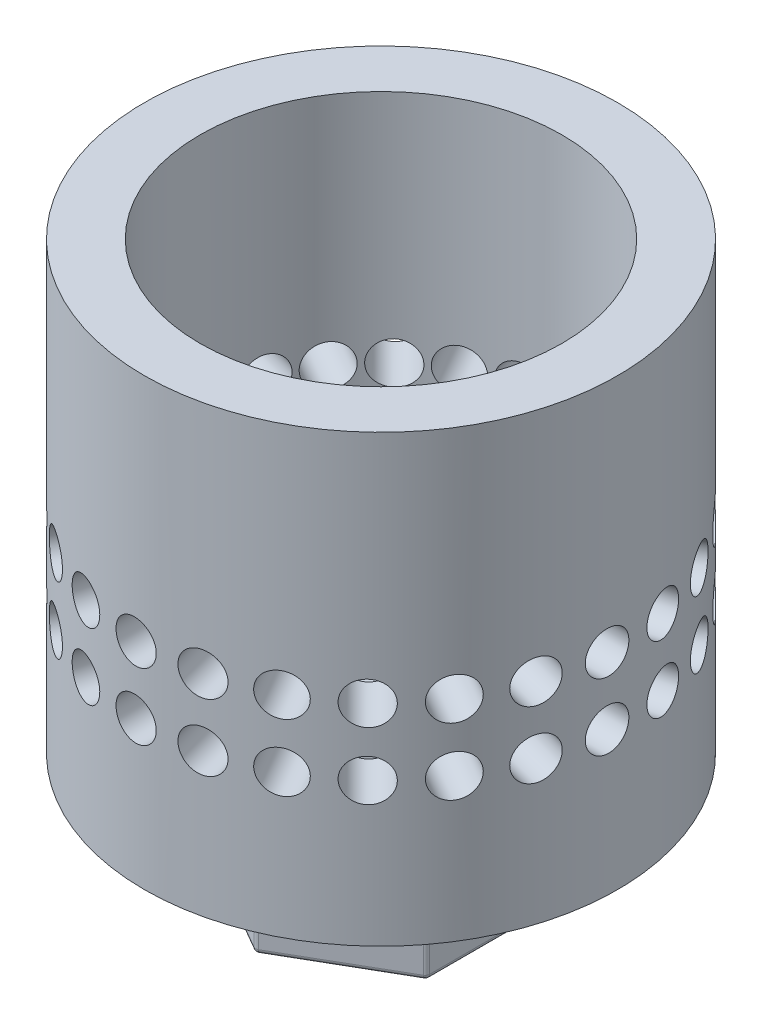
SolidWorks part; units mm, degrees
material "AISI 304"
ref_plane "Front Plane" through (0, 0, 0) normal (0, 0, 1) x (1, 0, 0)
ref_plane "Top Plane" through (0, 0, 0) normal (0, 1, 0) x (1, 0, 0)
ref_plane "Right Plane" through (0, 0, 0) normal (1, 0, 0) x (0, 0, -1)
sketch "Sketch1" plane through (0, 0, 0) normal (0, 1, 0) x (1, 0, 0)
  circle A0 centre (0, 0) radius 13.5
  dimension "D1" = 27
extrude "Boss-Extrude1" add sketch "Sketch1" along normal blind 25.4
hole_wizard "7/8-14 Tapped Hole1" positions "Sketch4" profile "Sketch5" tap size "7/8-14" standard "ANSI Inch"
sketch "Sketch4" plane through (0, 25.4, 0) normal (0, 1, 0) x (1, 0, 0)
  point P0 (0, 0)
sketch "Sketch5" plane through (0, 25.4, 0) normal (1, 0, 0) x (0, 0, 1)
  line L0 (0, 0) -> (0, 25.2501)
  line L1 (0, 25.2501) -> (10.3187, 19.05)
  line L2 (10.3187, 19.05) -> (10.3187, 0)
  line L5 (10.3187, 0) -> (0, 0)
  line L10 (0, 25.2501) -> (-10.3188, 19.05) construction
  line L11 (0, -6.35) -> (0, 107.95) construction
  dimension "Tap Drill Dia." = 20.6375
  dimension "Tap Drill Depth" = 19.05
  dimension "Drill Angle" = 118
cosmetic thread "Hole Thread1" parameters "D1"=44.45, "D2"=22.225
sketch "Sketch6" plane through (0, 0, 0) normal (0, -1, 0) x (1, 0, 0)
  line L1 (6.223, 3.5929) -> (0, 7.1857)
  line L2 (0, 7.1857) -> (-6.223, 3.5929)
  line L3 (-6.223, 3.5929) -> (-6.223, -3.5929)
  line L4 (-6.223, -3.5929) -> (0, -7.1857)
  line L5 (0, -7.1857) -> (6.223, -3.5929)
  line L6 (6.223, -3.5929) -> (6.223, 3.5929)
  circle A0 centre (0, 0) radius 6.223 construction
  dimension "D1" = 12.446
extrude "Boss-Extrude2" add sketch "Sketch6" along normal blind 6.35
fillet "Fillet1" radius 0.254 18 edges at (3.1115, 0, -5.3893) (-6.223, 0, 0) (-6.223, -3.175, -3.5929) (0, -3.175, -7.1857) (-3.1115, 0, -5.3893) (6.223, -3.175, -3.5929) (6.223, 0, 0) (-6.223, -3.175, 3.5929) (-3.1115, 0, 5.3893) (6.223, -3.175, 3.5929) (0, -3.175, 7.1857) (3.1115, 0, 5.3893) (3.1115, -6.35, -5.3893) (-3.1115, -6.35, -5.3893) (-6.223, -6.35, 0) (-3.1115, -6.35, 5.3893) (3.1115, -6.35, 5.3893) (6.223, -6.35, 0)
sketch "Sketch7" plane through (0, 0, 0) normal (0, 0, 1) x (1, 0, 0)
  circle A0 centre (0.5361, 8.1848) radius 1.1959
extrude "Cut-Extrude1" cut sketch "Sketch7" against normal through all
pattern_circular "CirPattern1" count 24 over 360 about axis through (0, 25.4, 0) along (0, -1, 0) of "Cut-Extrude1"
pattern_linear "LPattern1" count 2 spacing 3.81 along (0, 1, 0) of "CirPattern1", "Cut-Extrude1"
